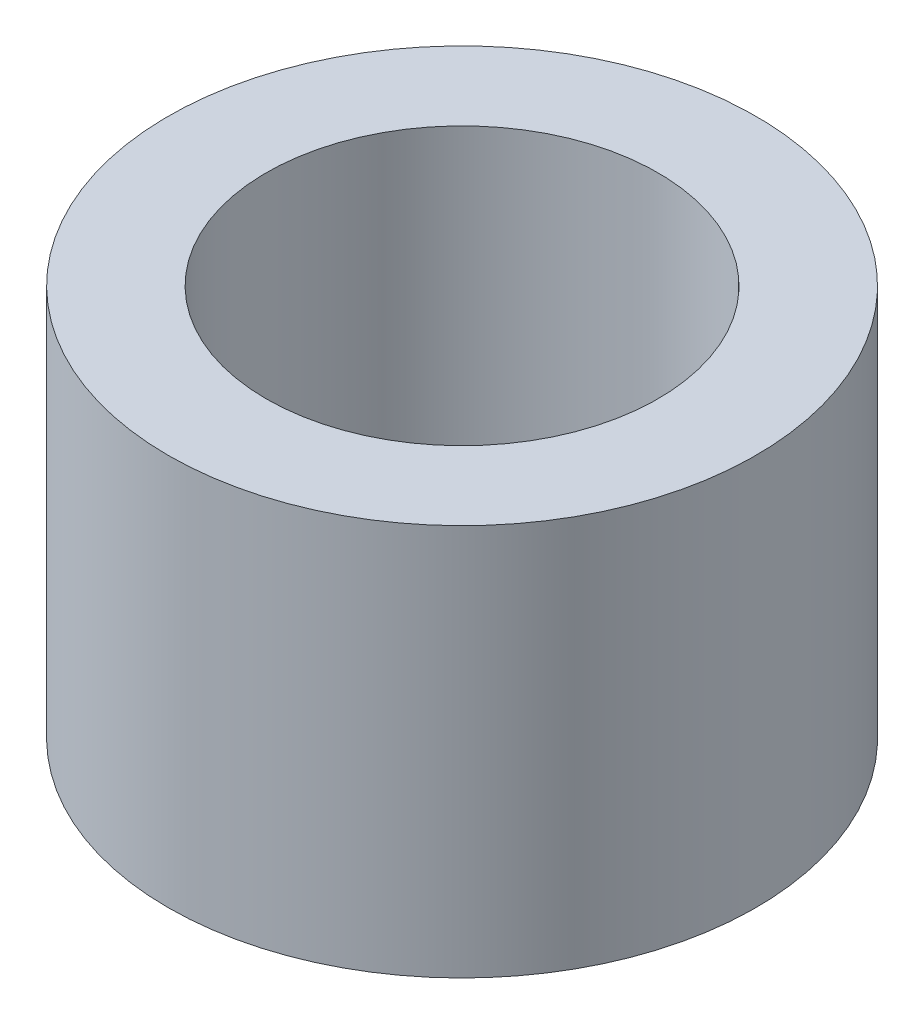
SolidWorks part; units mm, degrees
ref_plane "Front Plane" through (0, 0, 0) normal (0, 0, 1) x (1, 0, 0)
ref_plane "Top Plane" through (0, 0, 0) normal (0, 1, 0) x (1, 0, 0)
ref_plane "Right Plane" through (0, 0, 0) normal (1, 0, 0) x (0, 0, -1)
sketch "Sketch1" plane through (0, 0, 0) normal (0, 1, 0) x (1, 0, 0)
  circle A0 centre (0, 0) radius 3.175
  circle A2 centre (0, 0) radius 4.7625
  dimension "D1" = 1.5875
extrude "Boss-Extrude1" add sketch "Sketch1" along normal blind 6.35
